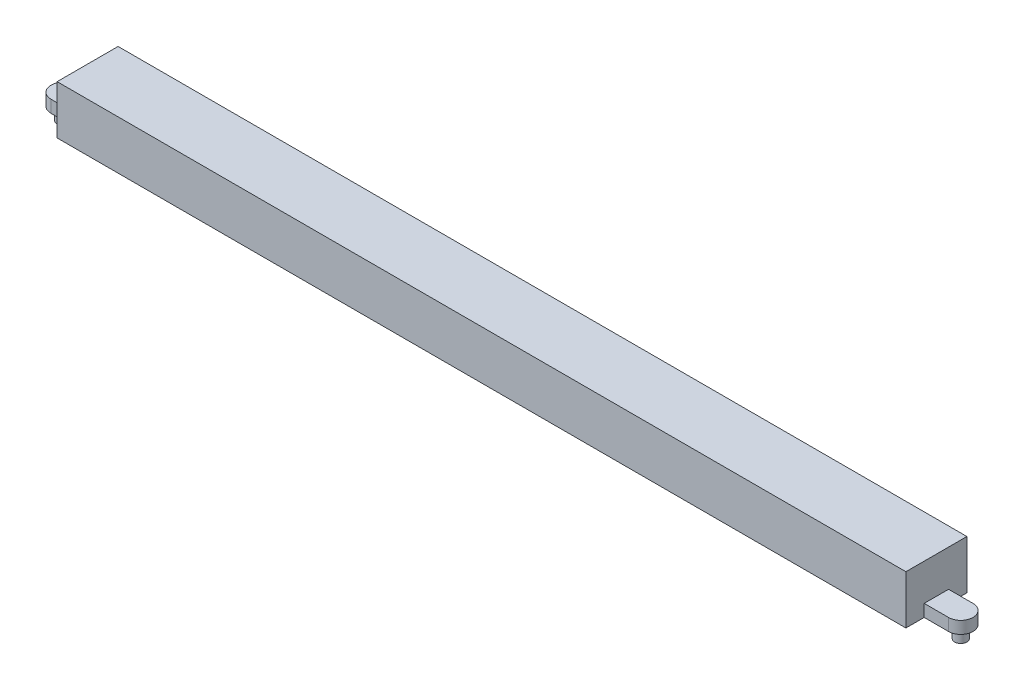
SolidWorks part; units mm, degrees
material "ABS"
ref_plane "Front Plane" through (0, 0, 0) normal (0, 0, 1) x (1, 0, 0)
ref_plane "Top Plane" through (0, 0, 0) normal (0, 1, 0) x (1, 0, 0)
ref_plane "Right Plane" through (0, 0, 0) normal (1, 0, 0) x (0, 0, -1)
sketch "Sketch1" plane through (0, 0, 0) normal (0, 1, 0) x (1, 0, 0)
  line L1 (-33.8, -2) -> (33.8, -2)
  line L2 (-33.8, -2) -> (-33.8, 2)
  line L3 (-33.8, 2) -> (33.8, 2)
  line L4 (33.8, -2) -> (33.8, 2)
  line L5 (-33.8, -2) -> (33.8, 2) construction
  line L6 (-33.8, 2) -> (33.8, -2) construction
  point P0 (0, 0)
  dimension "D1" = 4
  dimension "D2" = 67.6
extrude "Base" add sketch "Sketch1" along normal blind 1
sketch "Sketch2" plane through (0, 1, 0) normal (0, 1, 0) x (1, 0, 0)
  line L0 (-17.7, -2.5) -> (-17.7, 1.4) construction
  line L2 (-18.1, -2.5) -> (-18.1, 1)
  line L3 (-18.1, -2.5) -> (-17.3, -2.5)
  line L4 (-17.3, -2.5) -> (-17.3, 1)
  line L6 (33.8, -2) -> (33.8, 2) construction
  line L7 (33.8, 2) -> (-33.8, 2) construction
  line L8 (-33.8, 2) -> (-33.8, -2) construction
  arc A0 (-18.1, 1) -> (-17.3, 1) centre (-17.7, 1) cw
  dimension "D3" = 0.4
  dimension "D1" = 0.8
  dimension "D2" = 3.5
  dimension "D4" = 3.9
  dimension "D5" = 15.7
extrude "nock" add sketch "Sketch2" along normal blind 1
sketch "Sketch3" plane through (0, 0, 0) normal (0, 1, 0) x (1, 0, 0)
  line L0 (-33.8, 2) -> (-34.8, 2)
  line L1 (-34.8, 2) -> (-34.8, -3)
  line L2 (-34.8, -3) -> (34.8, -3)
  line L3 (34.8, -3) -> (34.8, 2)
  line L4 (34.8, 2) -> (33.8, 2)
  line L5 (33.8, 2) -> (33.8, -2)
  line L6 (33.8, -2) -> (-33.8, -2)
  line L7 (-33.8, -2) -> (-33.8, 2)
  dimension "D1" = 1
  dimension "D2" = 1
  dimension "D3" = 1
extrude "Walls" add sketch "Sketch3" along normal blind 3
sketch "Sketch4" plane through (0, 3, 0) normal (0, 1, 0) x (1, 0, 0)
  line L1 (-34.8, -3) -> (34.8, -3)
  line L2 (-34.8, -3) -> (-34.8, 2)
  line L3 (-34.8, 2) -> (34.8, 2)
  line L4 (34.8, -3) -> (34.8, 2)
extrude "Top" add sketch "Sketch4" along normal blind 1
sketch "Sketch5" plane through (0, 0, 0) normal (0, 1, 0) x (1, 0, 0)
  line L0 (-34.8, 2) -> (-34.8, -3) construction
  line L1 (-34.8, -0.5) -> (-30.3864, -0.5) construction
  line L2 (-34.8, 0.5) -> (-34.8, -1.5)
  line L3 (-36.8, -1.5) -> (-34.8, -1.5)
  line L4 (-36.8, -1.5) -> (-36.8, 0.5) construction
  line L5 (-36.8, 0.5) -> (-34.8, 0.5)
  line L7 (-36.8, -1.5) -> (-34.8, -0.5) construction
  line L8 (-36.8, 0.5) -> (-34.8, -0.5) construction
  line L9 (34.8, -3) -> (34.8, 2) construction
  line L10 (34.8, -1.5) -> (36.8, -1.5)
  line L12 (34.8, 0.5) -> (36.8, 0.5)
  line L13 (36.8, -1.5) -> (36.8, 0.5) construction
  line L14 (34.8, -0.5) -> (36.8, 0.5) construction
  line L15 (34.8, -0.5) -> (36.8, -1.5) construction
  line L16 (34.8, 0.5) -> (34.8, -1.5)
  arc A0 (36.8, -1.5) -> (36.8, 0.5) centre (36.8, -0.5) ccw
  arc A1 (-36.8, 0.5) -> (-36.8, -1.5) centre (-36.8, -0.5) ccw
  point P5 (34.8, -0.5)
  point P6 (-34.8, -0.5)
  dimension "D1" = 2
  dimension "D2" = 2
  dimension "D3" = 2
  dimension "D4" = 2
  dimension "D5" = 1
  dimension "D6" = 1
  dimension "D7" = 0
extrude "MountingTabs" add sketch "Sketch5" along normal blind 1
sketch "Sketch6" plane through (0, 0, 0) normal (0, -1, 0) x (1, 0, 0)
  circle A0 centre (-36.8, 0.5) radius 0.5
  circle A1 centre (36.8, 0.5) radius 0.5
  dimension "D1" = 1
  dimension "D2" = 1
extrude "Boss-Extrude7" add sketch "Sketch6" along normal blind 1
equation "\"D1@Walls\"=.1+.14+.01+.05"
